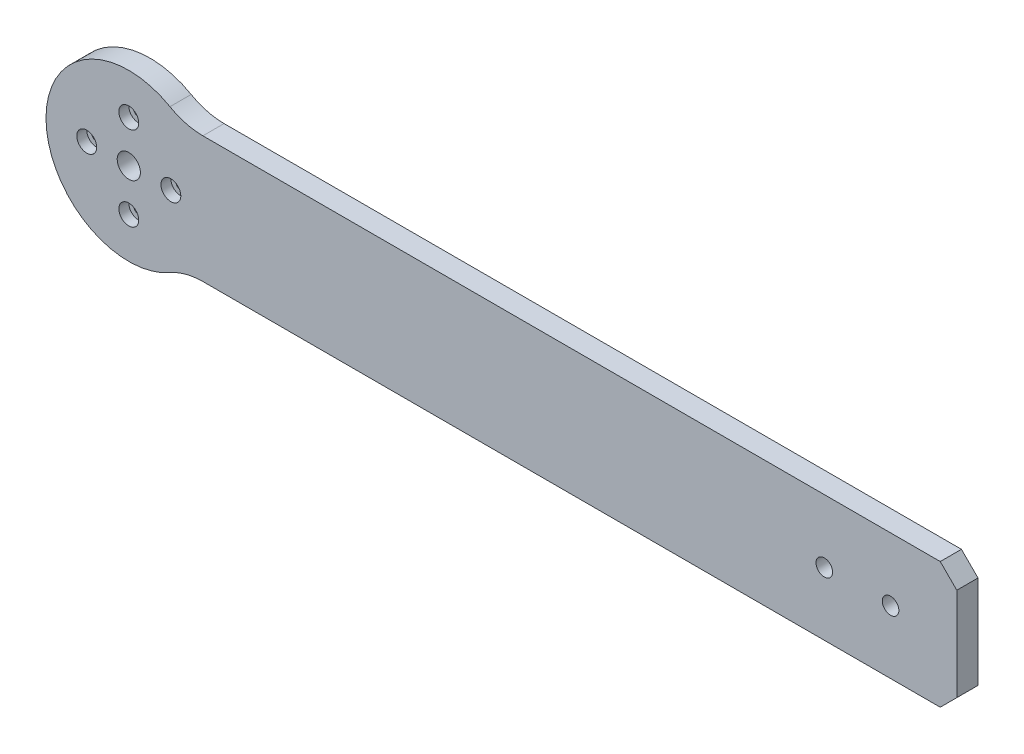
SolidWorks part; units mm, degrees
material "7075-T6, Plate (SS)"
ref_plane "Front Plane" through (0, 0, 0) normal (0, 0, 1) x (1, 0, 0)
ref_plane "Top Plane" through (0, 0, 0) normal (0, 1, 0) x (1, 0, 0)
ref_plane "Right Plane" through (0, 0, 0) normal (1, 0, 0) x (0, 0, -1)
sketch "Sketch1" plane through (0, 0, 0) normal (0, 0, 1) x (1, 0, 0)
  line L0 (0, 0) -> (250, 0) construction
  line L1 (0, 12.7) -> (0, 0) construction
  line L2 (250, 19.05) -> (16.1894, 19.05)
  line L3 (250, 19.05) -> (250, -19.05)
  line L4 (250, -19.05) -> (16.1894, -19.05)
  arc A0 (16.1894, 19.05) -> (16.1894, -19.05) centre (0, 0) ccw
  circle A1 centre (230, 0) radius 2.5
  circle A2 centre (210, 0) radius 2.5
  circle A3 centre (0, 0) radius 12.7 construction
  circle A4 centre (0, 12.7) radius 1.5
  circle A5 centre (12.7, 0) radius 1.5
  circle A6 centre (0, -12.7) radius 1.5
  circle A7 centre (-12.7, 0) radius 1.5
  circle A8 centre (0, 0) radius 3.5
  point P23 (0, 0)
  dimension "D1" = 50
  dimension "D4" = 5
  dimension "D7" = 25.4
  dimension "D8" = 3
  dimension "D10" = 7
  dimension "D2" = 38.1
  dimension "D3" = 250
  dimension "D5" = 20
  dimension "D6" = 20
  dimension "D9" = 4
extrude "Boss-Extrude1" add sketch "Sketch1" along normal blind 6.4
sketch "Sketch2" plane through (0, 0, 6.4) normal (0, 0, 1) x (1, 0, 0)
  line L0 (0, 12.7) -> (0, 0) construction
  line L1 (0, 0) -> (12.7, 0) construction
  circle A0 centre (0, 12.7) radius 3
  circle A1 centre (12.7, 0) radius 3
  circle A2 centre (0, -12.7) radius 3
  circle A3 centre (-12.7, 0) radius 3
  circle A4 centre (12.7, 0) radius 1.5 construction
  point P3 (9.4497, 0)
  point P12 (0, 0)
  dimension "D1" = 6
  dimension "D2" = 4
extrude "Cut-Extrude1" cut sketch "Sketch2" against normal blind 3
fillet "Fillet1" radius 20 2 edges at (16.1894, -19.05, 3.2) (16.1894, 19.05, 3.2)
chamfer "Chamfer1" distance 5 angle 45 2 edges at (250, -19.05, 3.2) (250, 19.05, 3.2)
